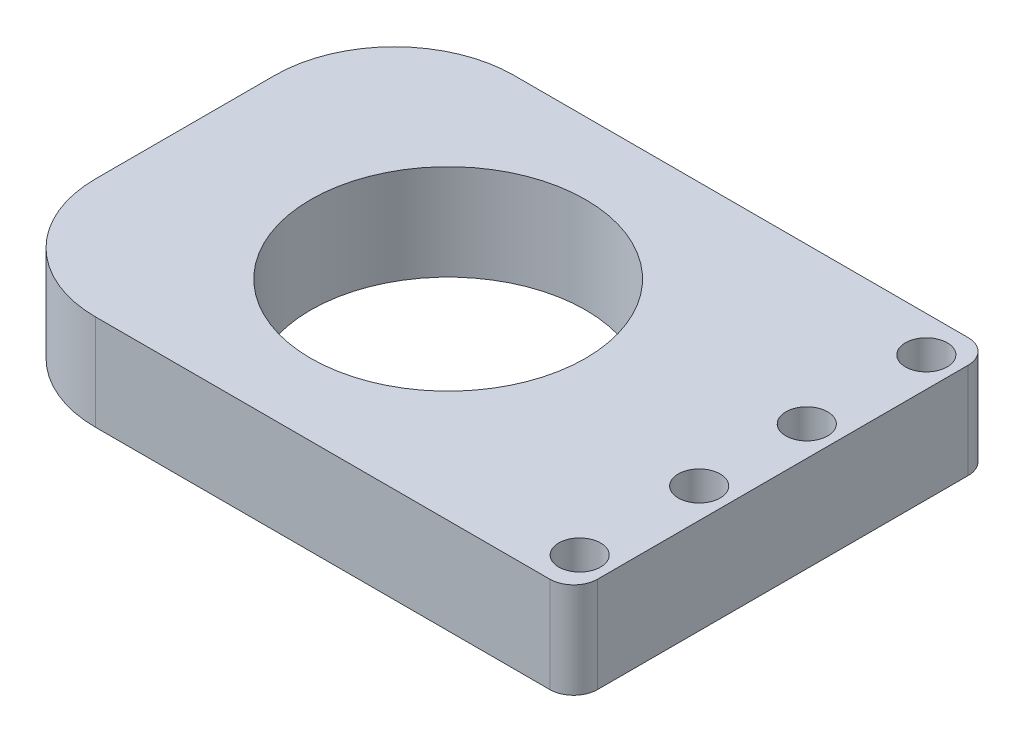
SolidWorks part; units mm, degrees
ref_plane "Front Plane" through (0, 0, 0) normal (0, 0, 1) x (1, 0, 0)
ref_plane "Top Plane" through (0, 0, 0) normal (0, 1, 0) x (1, 0, 0)
ref_plane "Right Plane" through (0, 0, 0) normal (1, 0, 0) x (0, 0, -1)
sketch "Sketch1" plane through (0, 0, 0) normal (0, 1, 0) x (1, 0, 0)
  line L1 (28, 17.5) -> (-22, 17.5)
  line L2 (28, 17.5) -> (28, -17.5)
  line L3 (28, -17.5) -> (-22, -17.5)
  line L4 (-22, 17.5) -> (-22, -17.5)
  circle A0 centre (0, 0) radius 11.5
  point P8 (28, 0)
  dimension "D1" = 23
  dimension "D2" = 35
  dimension "D3" = 50
  dimension "D4" = 28
extrude "Boss-Extrude1" add sketch "Sketch1" along normal blind 8
fillet "Fillet3" radius 10 2 edges at (-22, 4, 17.5) (-22, 4, -17.5)
fillet "Fillet4" radius 2 2 edges at (28, 4, 17.5) (28, 4, -17.5)
sketch "Sketch2" plane through (0, 8, 0) normal (0, 1, 0) x (1, 0, 0)
  line L0 (28, -15.5) -> (28, 15.5) construction
  line L1 (26, 17.5) -> (-12, 17.5) construction
  circle A0 centre (25.5, 14.5) radius 1.75
  circle A1 centre (25.5, 4.5) radius 1.75
  circle A2 centre (25.5, -4.5) radius 1.75
  circle A3 centre (25.5, -14.5) radius 1.75
  point P12 (0, 0)
  dimension "D1" = 3.5
  dimension "D2" = 2.5
  dimension "D3" = 3
  dimension "D4" = 10
  dimension "D5" = 9
  dimension "D6" = 10
extrude "Cut-Extrude1" cut sketch "Sketch2" against normal through all contours A1 | A2 | A3 | A0
